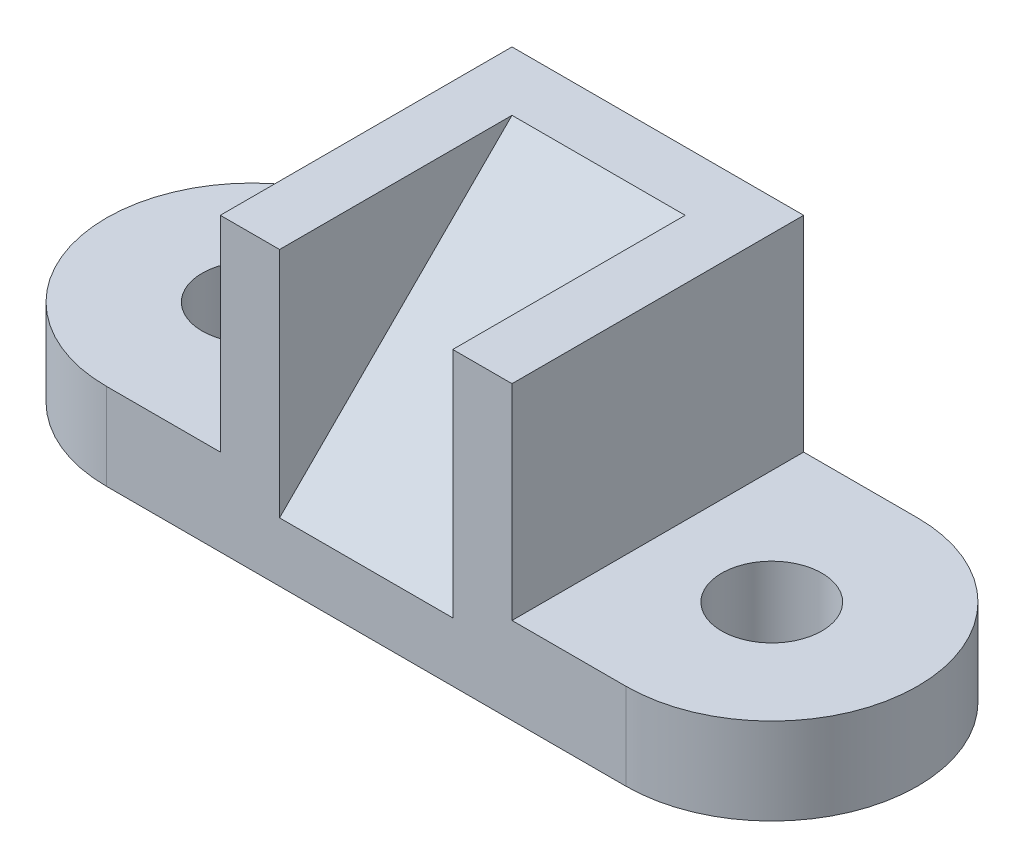
SolidWorks part; units mm, degrees
ref_plane "Front Plane" through (0, 0, 0) normal (0, 0, 1) x (1, 0, 0)
ref_plane "Top Plane" through (0, 0, 0) normal (0, 1, 0) x (1, 0, 0)
ref_plane "Right Plane" through (0, 0, 0) normal (1, 0, 0) x (0, 0, -1)
sketch "Sketch1" plane through (0, 0, 0) normal (0, 1, 0) x (1, 0, 0)
  line L0 (0, 0) -> (114, 0) construction
  line L1 (0, 32) -> (114, 32)
  line L2 (0, -32) -> (114, -32)
  arc A0 (0, 32) -> (0, -32) centre (0, 0) ccw
  arc A1 (114, -32) -> (114, 32) centre (114, 0) ccw
  circle A2 centre (0, 0) radius 11
  circle A3 centre (114, 0) radius 11
  point P3 (57, 0)
  dimension "D2" = 32
  dimension "D3" = 22
  dimension "D4" = 22
  dimension "D1" = 114
extrude "Boss-Extrude1" add sketch "Sketch1" along normal blind 19
sketch "Sketch2" plane through (0, 19, 0) normal (0, 1, 0) x (1, 0, 0)
  line L0 (114, 32) -> (0, 32) construction
  line L1 (25, 32) -> (89, 32)
  line L2 (25, 32) -> (25, -32)
  line L3 (25, -32) -> (89, -32)
  line L4 (89, 32) -> (89, -32)
  line L5 (0, -32) -> (114, -32) construction
  dimension "D1" = 64
  dimension "D2" = 25
extrude "Boss-Extrude2" add sketch "Sketch2" along normal blind 45
ref_plane "Plane2" through (57, 0, 0) normal (1, 0, 0) x (0, 0, -1)
sketch "Sketch4" plane through (57, 0, 0) normal (1, 0, 0) x (0, 0, -1)
  line L0 (-32, 64) -> (19, 64)
  line L1 (-32, 64) -> (32, 64) construction
  line L2 (19, 64) -> (-32, 13)
  line L3 (-32, 19) -> (-32, 0) construction
  line L4 (-32, 13) -> (-32, 64)
  dimension "D1" = 13
  dimension "D2" = 13
extrude "Cut-Extrude5" cut sketch "Sketch4" against normal mid plane 38
